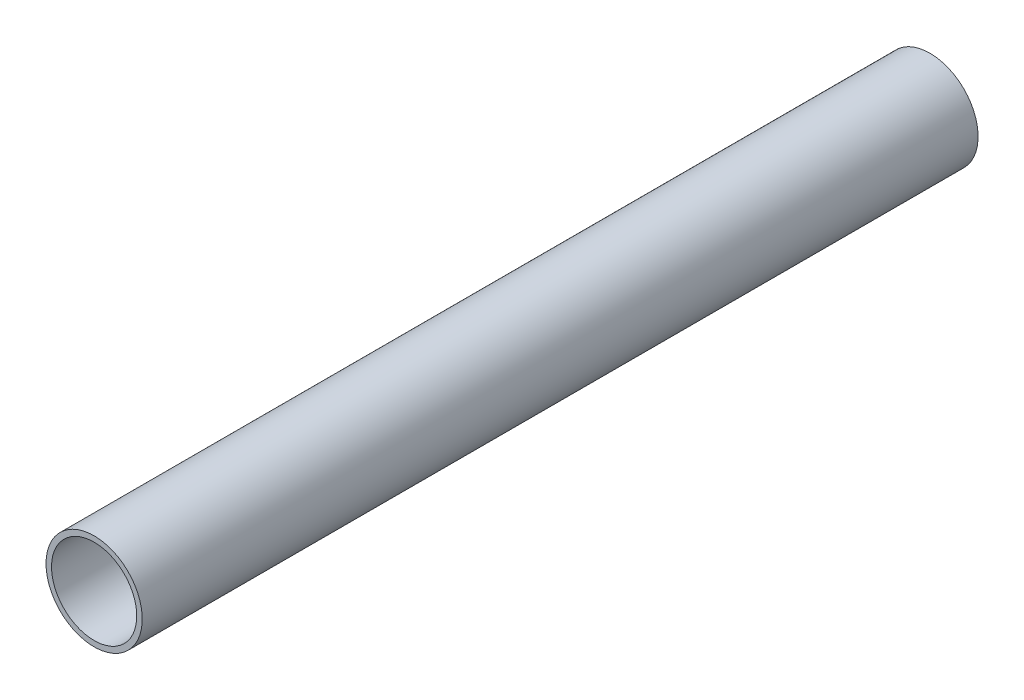
SolidWorks part; units mm, degrees
material "Paper"
ref_plane "Alzado" through (0, 0, 0) normal (0, 0, 1) x (1, 0, 0)
ref_plane "Planta" through (0, 0, 0) normal (0, 1, 0) x (1, 0, 0)
ref_plane "Vista lateral" through (0, 0, 0) normal (1, 0, 0) x (0, 0, -1)
sketch "Croquis1" plane through (0, 0, 0) normal (0, 0, 1) x (1, 0, 0)
  circle A0 centre (0, 0) radius 23.2
  circle A1 centre (0, 0) radius 26.2
  dimension "D1" = 52.4
  dimension "D2" = 46.4
extrude "Saliente-Extruir1" add sketch "Croquis1" along normal blind 455
equation "\"ODAblative\"= 52.4mm"
equation "\"D1@Croquis1\"=\"ODAblative\""
equation "\"IDAblative\"= \"ODAblative\" - \"AblativeThickness\" * 2"
equation "\"D2@Croquis1\"=\"IDAblative\""
equation "\"LengthAblative\"= 455mm"
equation "\"D1@Saliente-Extruir1\"=\"LengthAblative\""
equation "\"AblativeThickness\"= 3"
